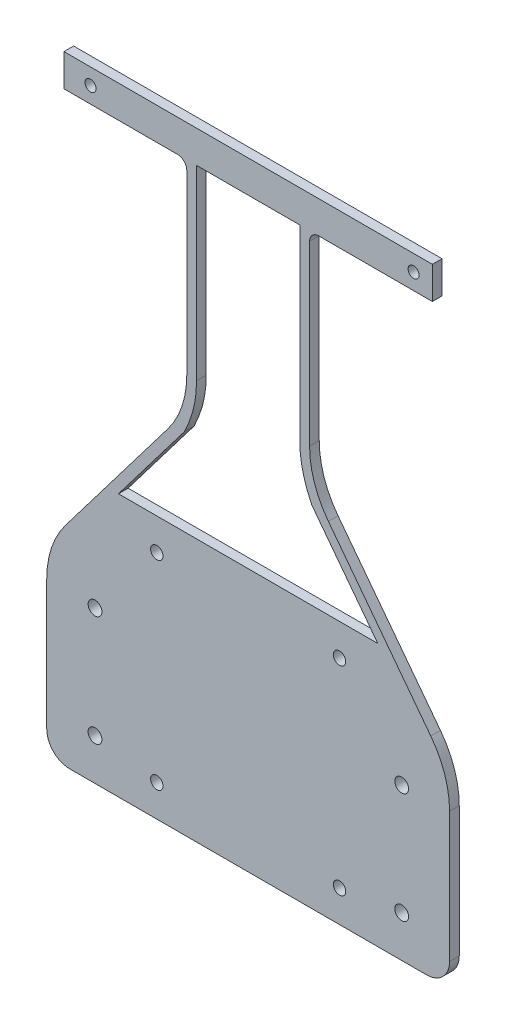
SolidWorks part; units mm, degrees
ref_plane "Front Plane" through (0, 0, 0) normal (0, 0, 1) x (1, 0, 0)
ref_plane "Top Plane" through (0, 0, 0) normal (0, 1, 0) x (1, 0, 0)
ref_plane "Right Plane" through (0, 0, 0) normal (1, 0, 0) x (0, 0, -1)
sketch "Sketch2" plane through (0, 0, 0) normal (0, 0, 1) x (1, 0, 0)
  line L1 (26.3605, -75.742) -> (106.3655, -75.742)
  line L2 (32.1325, -66.109) -> (102.2825, -66.109) construction
  line L4 (37.2075, -82.742) -> (51.029, -82.742)
  line L7 (32.1325, -66.109) -> (32.1325, -83.8522) construction
  line L12 (25.308, -210) -> (27.6255, -210)
  line L13 (54.697, -210) -> (105.1011, -209.994)
  line L15 (25.308, -210) -> (54.697, -210)
  line L16 (22.6255, -205) -> (22.6255, -176.7381)
  line L17 (110.1005, -204.994) -> (110.1005, -176.7325)
  line L18 (42.6255, -207) -> (42.6255, -155.977) construction
  line L19 (42.6255, -207) -> (90.1005, -207) construction
  line L20 (90.1005, -207) -> (90.1005, -155.977) construction
  line L21 (48.9516, -135.3644) -> (26.7029, -164.6356)
  line L22 (83.7755, -135.3653) -> (106.0221, -164.6286)
  line L23 (42.6255, -155.977) -> (90.1005, -155.977) construction
  line L24 (102.2825, -66.109) -> (102.2825, -83.8522) construction
  line L25 (66.363, -75.742) -> (66.363, -155.977) construction
  line L26 (22.7026, -177) -> (41.3185, -177) construction
  line L27 (22.7026, -201) -> (41.3185, -201) construction
  line L28 (110.1005, -177) -> (91.4846, -177) construction
  line L29 (110.1005, -201) -> (91.4846, -201) construction
  line L30 (26.3605, -75.742) -> (26.3605, -82.742)
  line L31 (26.3605, -82.742) -> (37.2075, -82.742)
  line L32 (106.3655, -75.742) -> (106.3655, -82.742)
  line L33 (106.3655, -82.742) -> (96.9045, -82.742)
  line L34 (53.029, -123.2619) -> (53.029, -84.742)
  line L35 (79.697, -123.2614) -> (79.697, -84.742)
  line L36 (96.9045, -82.742) -> (81.697, -82.742)
  line L37 (55.129, -82.742) -> (77.597, -82.742)
  line L38 (55.129, -82.742) -> (55.129, -123.2619)
  line L39 (77.597, -82.742) -> (77.597, -123.2619)
  line L40 (38.2022, -152.977) -> (94.5263, -152.977)
  line L41 (94.5263, -152.977) -> (80.1873, -134.1153)
  line L42 (38.2022, -152.977) -> (52.5387, -134.1153)
  line L43 (52.5387, -134.1153) -> (81.358, -134.1153) construction
  arc A2 (110.1005, -176.7325) -> (106.0221, -164.6286) centre (90.1005, -176.7325) ccw
  arc A3 (22.6255, -176.7381) -> (26.7029, -164.6356) centre (42.6255, -176.7381) cw
  arc A4 (79.697, -123.2614) -> (83.7755, -135.3653) centre (99.697, -123.2614) ccw
  arc A5 (53.029, -123.2619) -> (48.9516, -135.3644) centre (33.029, -123.2619) cw
  arc A6 (105.1011, -209.994) -> (110.1005, -204.994) centre (105.1005, -204.994) ccw
  arc A7 (27.6255, -210) -> (22.6255, -205) centre (27.6255, -205) cw
  circle A8 centre (46.5255, -159.877) radius 1.35
  circle A9 centre (46.5255, -203.1) radius 1.35
  circle A10 centre (86.2005, -203.1) radius 1.35
  circle A11 centre (86.2005, -159.877) radius 1.35
  circle A12 centre (33.1061, -201) radius 1.5
  circle A13 centre (33.1061, -177) radius 1.5
  circle A14 centre (99.697, -177) radius 1.5
  circle A15 centre (99.697, -201) radius 1.5
  circle A16 centre (32.1325, -79.242) radius 1.2
  circle A17 centre (102.2825, -79.242) radius 1.2
  arc A18 (51.029, -82.742) -> (53.029, -84.742) centre (51.029, -84.742) cw
  arc A19 (81.697, -82.742) -> (79.697, -84.742) centre (81.697, -84.742) ccw
  spline S0 degree 2 poles (52.5387, -134.1153) (55.239, -128.558) (55.129, -123.2619) knots 0 0 0 0.393827 0.393827 0.393827
  spline S1 degree 2 poles (80.1873, -134.1153) (77.487, -128.558) (77.597, -123.2619) knots 0 0 0 0.393827 0.393827 0.393827
  point P4 (44.1182, -82.742)
  point P20 (66.363, -155.977)
  point P31 (110.1005, -169.9934)
  point P39 (80.005, -130)
  point P45 (110.1005, -209.9934)
  point P53 (79.697, -82.742)
  dimension "D3" = 24
  dimension "D17" = 20
  dimension "D18" = 5
  dimension "D19" = 3.9
  dimension "D24" = 2.1
  dimension "D4" = 3.9
  dimension "D8" = 2
  dimension "D23" = 2
  dimension "D5" = 3.9
  dimension "D6" = 3.9
  dimension "D7" = 3.9
  dimension "D9" = 3.9
  dimension "D10" = 40
  dimension "D11" = 3.9
  dimension "D12" = 20
  dimension "D13" = 20
  dimension "D14" = 47.475
  dimension "D15" = 51.023
  dimension "D16" = 3
  dimension "D20" = 3.9
  dimension "D21" = 24
  dimension "D22" = 28.2619
  dimension "D25" = 2.1
  dimension "D26" = 2.1
  dimension "D27" = 3
  dimension "D28" = 2.1
extrude "Boss-Extrude1" add sketch "Sketch2" along normal blind 2.1 contours A19 L36 L33 L32 L1 L30 L31 L4 A18 L34 A5 L21 A3 L16 A7 L15 L13 A6 L17 A2 L22 A4 L35 S1 L41 L40 L42 S0 L38 L37 L39 A15 A11 A10 A8 A9 A12 A13 A14 A16
